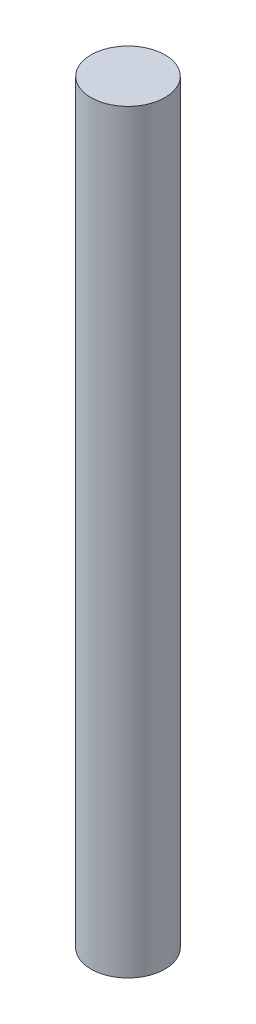
SolidWorks part; units mm, degrees
ref_plane "Front Plane" through (0, 0, 0) normal (0, 0, 1) x (1, 0, 0)
ref_plane "Top Plane" through (0, 0, 0) normal (0, 1, 0) x (1, 0, 0)
ref_plane "Right Plane" through (0, 0, 0) normal (1, 0, 0) x (0, 0, -1)
sketch "Sketch1" plane through (0, 0, 0) normal (0, 1, 0) x (1, 0, 0)
  circle A0 centre (0, 0) radius 9.8
  dimension "D1" = 19.6
extrude "Boss-Extrude1" add sketch "Sketch1" along normal blind 200
